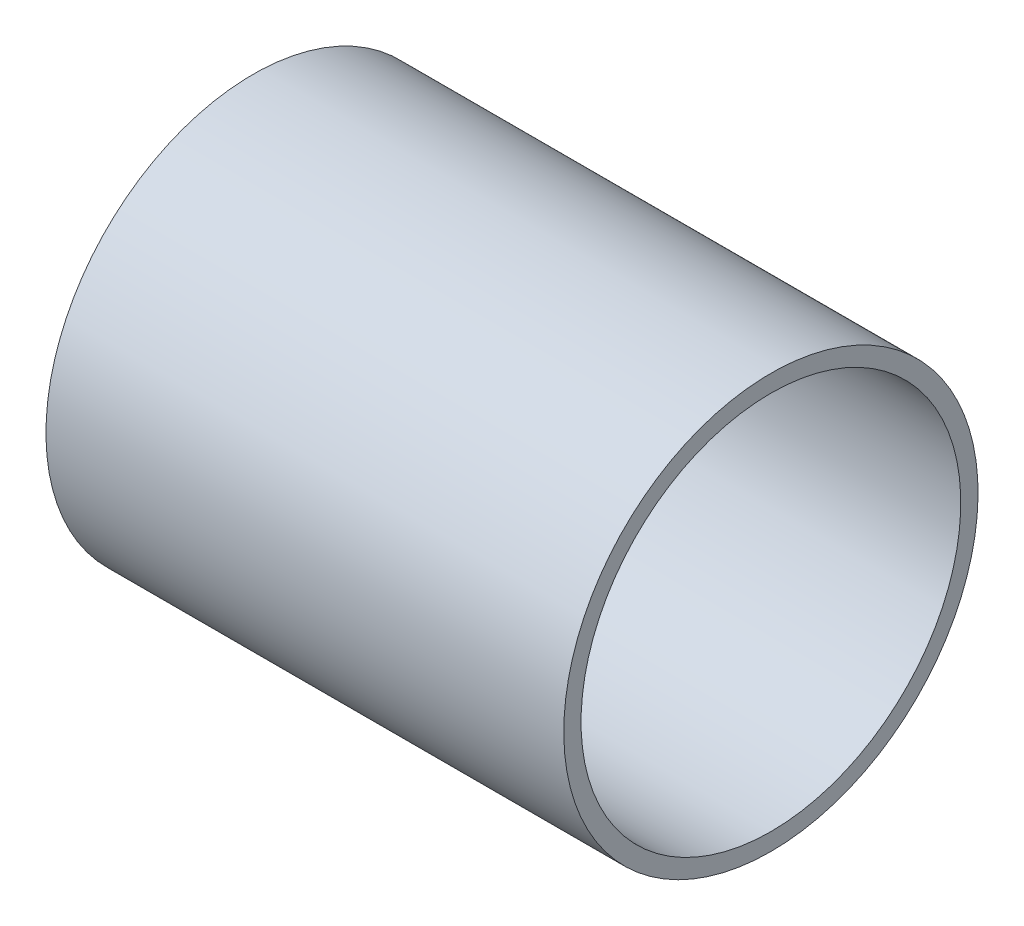
SolidWorks part; units mm, degrees
ref_plane "Front Plane" through (0, 0, 0) normal (0, 0, 1) x (1, 0, 0)
ref_plane "Top Plane" through (0, 0, 0) normal (0, 1, 0) x (1, 0, 0)
ref_plane "Right Plane" through (0, 0, 0) normal (1, 0, 0) x (0, 0, -1)
sketch "Sketch1" plane through (0, 0, 0) normal (0, 0, 1) x (1, 0, 0)
  line L0 (-66.5775, 0) -> (66.5775, 0) construction
  line L1 (-15, 12) -> (15, 12)
  line L2 (-15, 12) -> (-15, 11)
  line L3 (-15, 11) -> (15, 11)
  line L4 (15, 11) -> (15, 12)
  point P3 (0, 0)
  point P6 (0, 12)
  dimension "D1" = 24
  dimension "D2" = 1
  dimension "D3" = 30
revolve "Revolve1" add sketch "Sketch1" angle 360 about L0
